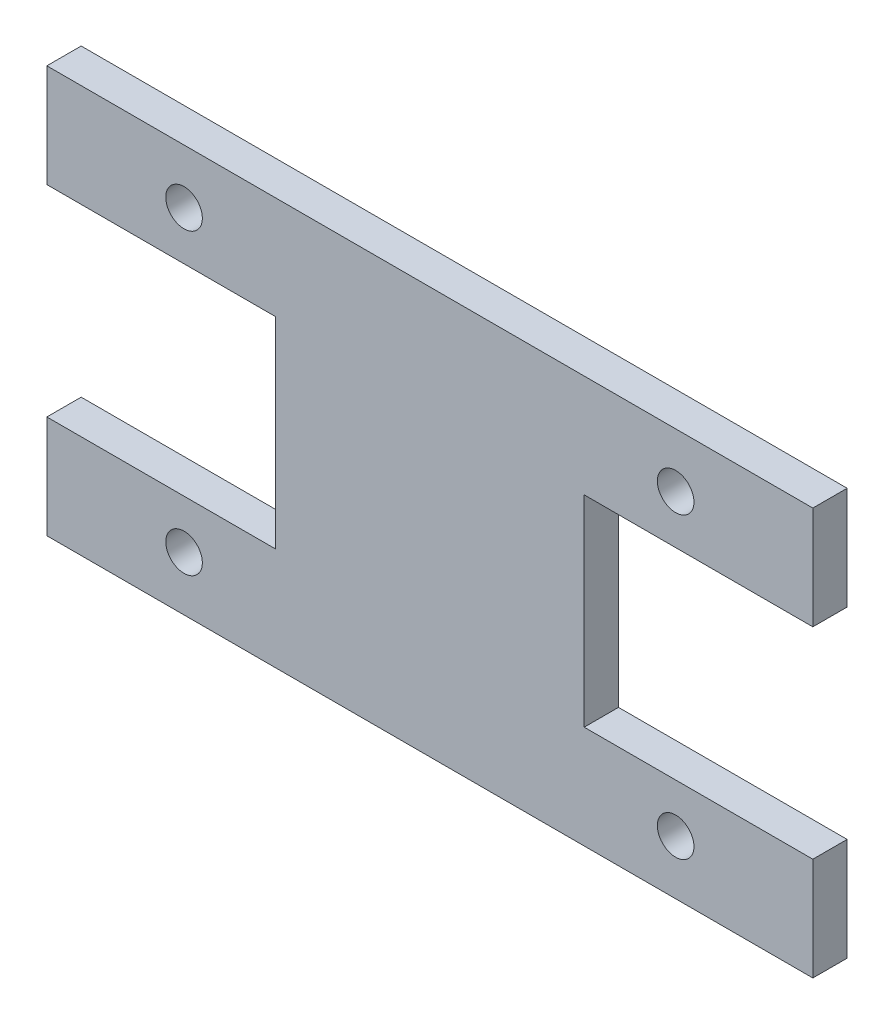
SolidWorks part; units mm, degrees
ref_plane "前视基准面" through (0, 0, 0) normal (0, 0, 1) x (1, 0, 0)
ref_plane "上视基准面" through (0, 0, 0) normal (0, 1, 0) x (1, 0, 0)
ref_plane "右视基准面" through (0, 0, 0) normal (1, 0, 0) x (0, 0, -1)
other "Configuration Table"
sketch "草图1" plane through (0, 0, 0) normal (0, 0, 1) x (1, 0, 0)
  line L0 (-45, 0) -> (-45, 9)
  line L1 (-45, 35.6) -> (-112, 35.6)
  line L2 (-112, 35.6) -> (-112, 26.6)
  line L3 (-112, 0) -> (-45, 0)
  line L4 (-45, 9) -> (-65, 9)
  line L5 (-65, 9) -> (-65, 26.6)
  line L6 (-65, 26.6) -> (-45, 26.6)
  line L7 (-142, 9) -> (-166, 9) construction
  line L8 (-166, 26.6) -> (-142, 26.6) construction
  line L9 (-112, 9) -> (-92, 9)
  line L10 (-92, 9) -> (-92, 26.6)
  line L11 (-92, 26.6) -> (-112, 26.6)
  line L12 (-45, 26.6) -> (-45, 35.6)
  line L13 (-112, 9) -> (-112, 0)
  circle A1 centre (-57, 4.75) radius 1.6
  circle A2 centre (-57, 4.75) radius 1.6
  circle A3 centre (-57, 30.85) radius 1.6
  circle A4 centre (-57, 30.85) radius 1.6
  circle A5 centre (-100, 4.75) radius 1.6
  circle A7 centre (-100, 4.75) radius 1.6
  circle A9 centre (-100, 30.85) radius 1.6
  circle A10 centre (-100, 30.85) radius 1.6
  dimension "D1" = 20
  dimension "D2" = 20
  dimension "D3" = 0
  dimension "D4" = 0
  dimension "D5" = 0
  dimension "D6" = 0
extrude "凸台-拉伸1" add sketch "草图1" along normal blind 3
